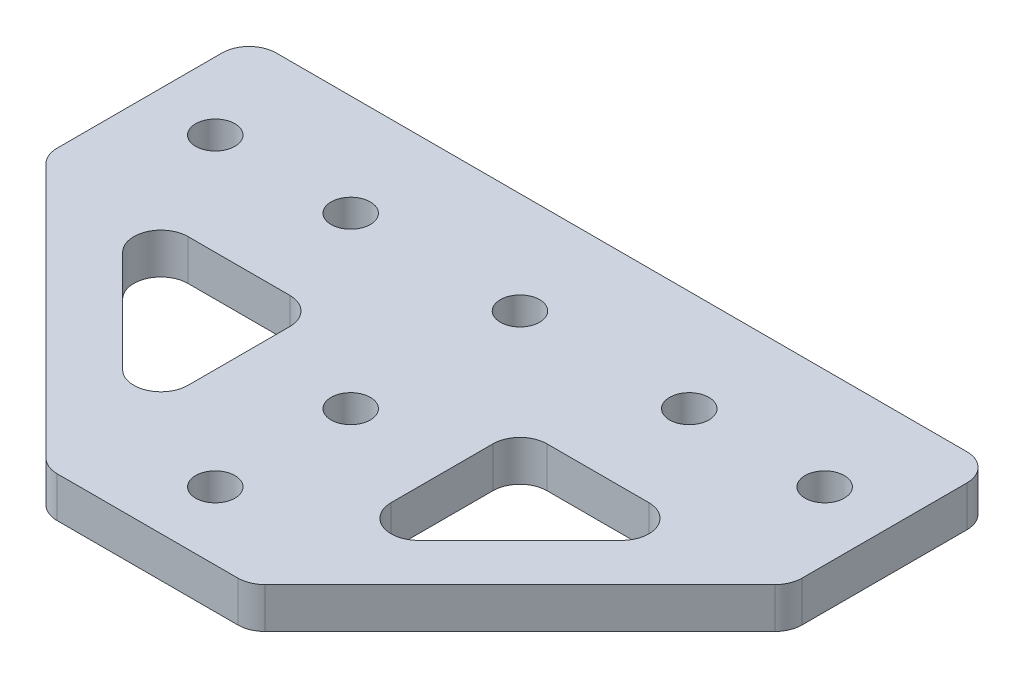
SolidWorks part; units mm, degrees
material "Thornel Mat VMA"
ref_plane "前视基准面" through (0, 0, 0) normal (0, 0, 1) x (1, 0, 0)
ref_plane "上视基准面" through (0, 0, 0) normal (0, 1, 0) x (1, 0, 0)
ref_plane "右视基准面" through (0, 0, 0) normal (1, 0, 0) x (0, 0, -1)
other "Configuration Table"
sketch "草图1" plane through (0, 0, 0) normal (0, 1, 0) x (1, 0, 0)
  line L0 (-35, -7.5) -> (0, -7.5) construction
  line L1 (0, 0) -> (-35, 0)
  line L2 (0, 0) -> (0, -35)
  line L3 (0, -35) -> (-15, -35)
  line L4 (-35, 0) -> (-35, -15)
  line L7 (-35, -15) -> (-15, -15)
  line L8 (-15, -35) -> (-15, -15)
  line L9 (-7.5, -35) -> (-7.5, 0) construction
  line L10 (0, -15) -> (20, -15)
  line L11 (20, -15) -> (20, 0)
  line L12 (20, 0) -> (0, 0)
  circle A0 centre (-7.5, -7.5) radius 1.45
  circle A1 centre (-20, -7.5) radius 1.45
  circle A2 centre (-30, -7.5) radius 1.45
  circle A3 centre (-7.5, -20) radius 1.45
  circle A4 centre (-7.5, -30) radius 1.45
  circle A5 centre (15, -7.5) radius 1.45
  circle A6 centre (5, -7.5) radius 1.45
  dimension "D3" = 2.9
  dimension "D4" = 2.9
  dimension "D5" = 2.9
  dimension "D6" = 5
  dimension "D7" = 10
  dimension "D9" = 2.9
  dimension "D10" = 2.9
  dimension "D12" = 10
  dimension "D1" = 15
  dimension "D2" = 15
  dimension "D8" = 35
  dimension "D11" = 5
  dimension "D13" = 35
  dimension "D14" = 20
extrude "凸台-拉伸1" add sketch "草图1" along normal blind 3 contours L8 L3 L2 L1 L4 L7 A4 A3 A2 A1 A0 | L11 L12 L2 L10 A5 A6
sketch "草图2" plane through (0, 3, 0) normal (0, 1, 0) x (1, 0, 0)
  line L0 (-35, -15) -> (-15, -35)
  line L1 (-15, -35) -> (-15, -29.3431)
  line L3 (-15, -29.3431) -> (-29.3431, -15)
  line L5 (-29.3431, -15) -> (-35, -15)
  line L6 (-7.5, -35) -> (-7.5, 0) construction
  line L7 (0, -35) -> (-15, -35) construction
  line L8 (20, 0) -> (-35, 0) construction
  line L9 (-15, -35) -> (-15, -15) construction
  line L10 (14.3431, -15) -> (20, -15)
  line L11 (0, -29.3431) -> (14.3431, -15)
  line L12 (0, -35) -> (0, -29.3431)
  line L13 (20, -15) -> (0, -35)
  dimension "D1" = 4
extrude "凸台-拉伸2" add sketch "草图2" against normal blind 3 contours L10 L13 L12 L11 | L0 L1 L3 L5
fillet "圆角1" radius 2 12 edges at (-15, 1.5, 35) (-35, 1.5, 15) (-35, 1.5, 0) (-15, 1.5, 29.3431) (-29.3431, 1.5, 15) (-15, 1.5, 15) (0, 1.5, 15) (14.3431, 1.5, 15) (20, 1.5, 0) (20, 1.5, 15) (0, 1.5, 35) (0, 1.5, 29.3431)
